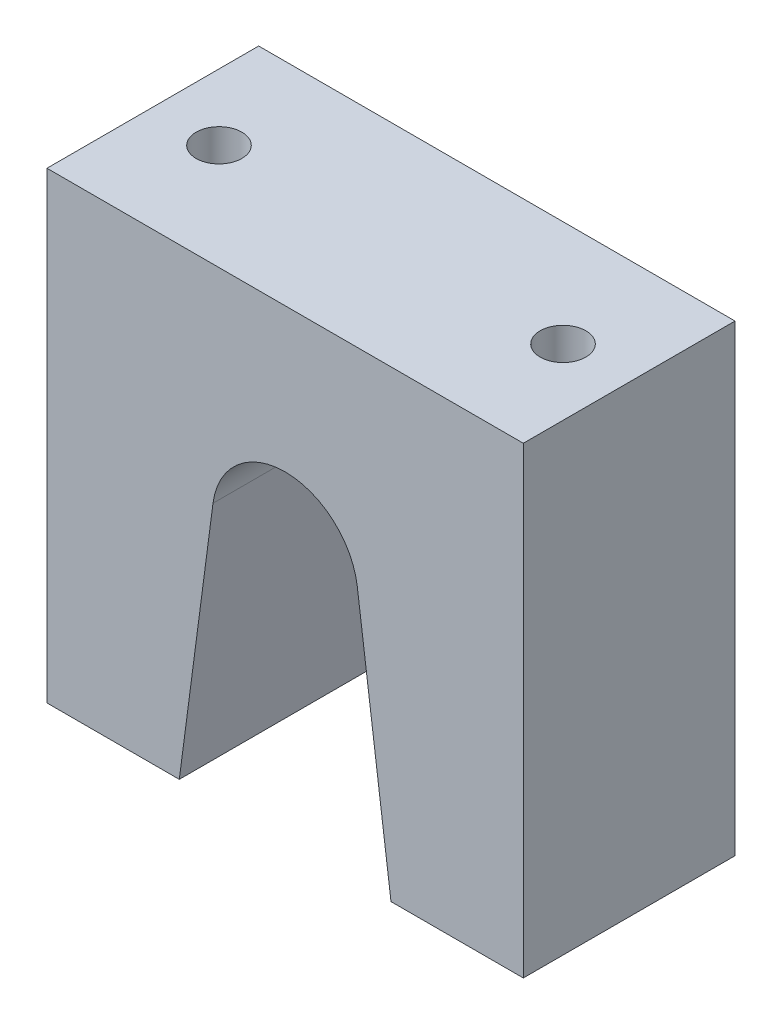
SolidWorks part; units mm, degrees
ref_plane "Front Plane" through (0, 0, 0) normal (0, 0, 1) x (1, 0, 0)
ref_plane "Top Plane" through (0, 0, 0) normal (0, 1, 0) x (1, 0, 0)
ref_plane "Right Plane" through (0, 0, 0) normal (1, 0, 0) x (0, 0, -1)
other "Bounding Box"
ref_plane "Default Plane" through (-18, -18.6289, 0) normal (0, 1, 0) x (1, 0, 0)
sketch "Sketch1" plane through (0, 0, 0) normal (0, 0, 1) x (1, 0, 0)
  line L0 (5.4529, 0.7179) -> (8, -18.6289)
  line L1 (-5.4529, 0.7179) -> (-8, -18.6289)
  line L2 (0, 0) -> (0, -19.937) construction
  line L4 (-8, -18.6289) -> (-18, -18.6289)
  line L5 (-18, -18.6289) -> (-18, 16.3711)
  line L6 (-18, 16.3711) -> (18, 16.3711)
  line L7 (8, -18.6289) -> (18, -18.6289)
  line L8 (18, -18.6289) -> (18, 16.3711)
  arc A0 (5.4529, 0.7179) -> (-5.4529, 0.7179) centre (0, 0) ccw
  arc A1 (-5.4529, 0.7179) -> (5.4529, 0.7179) centre (0, 0) ccw construction
  point P12 (0, 16.3711)
  dimension "D1" = 11
  dimension "D2" = 16
  dimension "D3" = 15
  dimension "D4" = 35
  dimension "D5" = 18.6289
  dimension "D6" = 16.3711
  dimension "D7" = 10
extrude "Boss-Extrude1" add sketch "Sketch1" along normal blind 16
hole_wizard "#8-36 Tapped Hole1" positions "Sketch9" profile "Sketch10" tap size "#8-36" standard "ANSI Inch"
sketch "Sketch9" plane through (0, 16.3711, 0) normal (0, 1, 0) x (1, 0, 0)
  line L0 (0, 0) -> (0, -16) construction
  line L1 (18, 0) -> (-18, 0) construction
  line L7 (-18, -16) -> (-18, 0) construction
  line L9 (18, -16) -> (-18, -16) construction
  point P0 (-13, -8)
  point P2 (13, -8)
  point P29 (0, -8)
  dimension "D1" = 5
sketch "Sketch10" plane through (-13, 16.3711, 8) normal (1, 0, 0) x (0, 0, 1)
  line L0 (0, 0) -> (0, 26.0378)
  line L1 (0, 26.0378) -> (1.7272, 25)
  line L2 (1.7272, 25) -> (1.7272, 0)
  line L5 (1.7272, 0) -> (0, 0)
  line L10 (0, 26.0378) -> (-1.7272, 25) construction
  line L11 (0, -6.35) -> (0, 107.95) construction
  dimension "Tap Drill Dia." = 3.4544
  dimension "Tap Drill Depth" = 25
  dimension "Drill Angle" = 118
cosmetic thread "Hole Thread1"
cosmetic thread "Hole Thread2"
